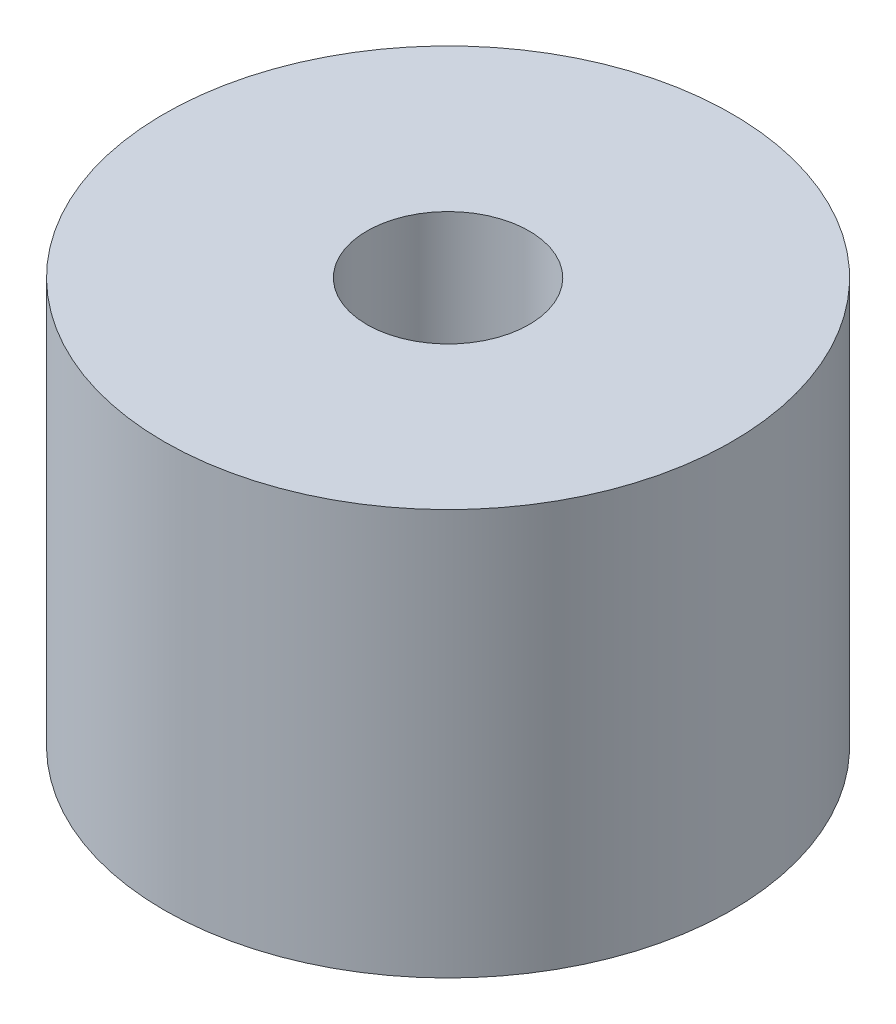
SolidWorks part; units mm, degrees
ref_plane "Front Plane" through (0, 0, 0) normal (0, 0, 1) x (1, 0, 0)
ref_plane "Top Plane" through (0, 0, 0) normal (0, 1, 0) x (1, 0, 0)
ref_plane "Right Plane" through (0, 0, 0) normal (1, 0, 0) x (0, 0, -1)
sketch "Sketch1" plane through (0, 0, 0) normal (0, 1, 0) x (1, 0, 0)
  circle A0 centre (0, 0) radius 3.5
  circle A1 centre (0, 0) radius 1
extrude "Boss-Extrude1" add sketch "Sketch1" along normal blind 5
